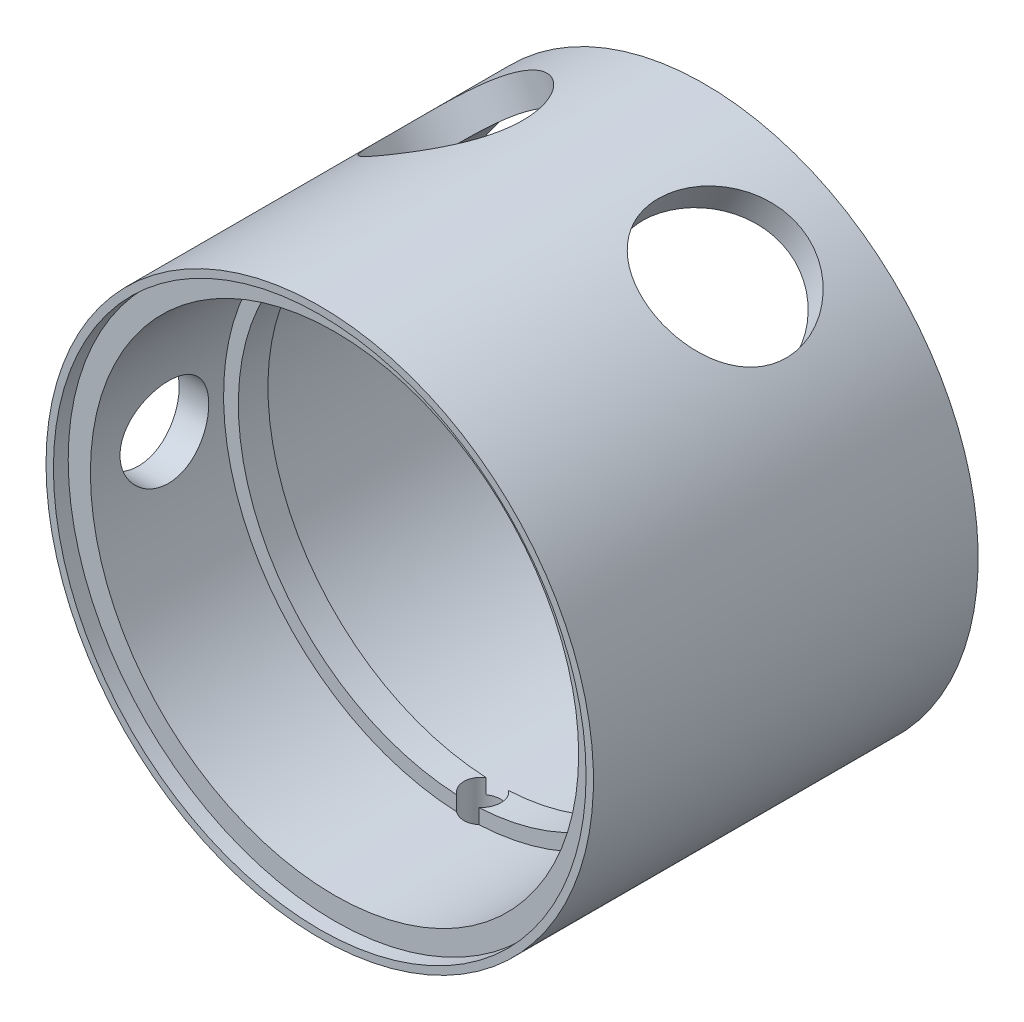
SolidWorks part; units mm, degrees
ref_plane "Front Plane" through (0, 0, 0) normal (0, 0, 1) x (1, 0, 0)
ref_plane "Top Plane" through (0, 0, 0) normal (0, 1, 0) x (1, 0, 0)
ref_plane "Right Plane" through (0, 0, 0) normal (1, 0, 0) x (0, 0, -1)
sketch "Sketch1" plane through (0, 0, 0) normal (0, 0, 1) x (1, 0, 0)
  circle A0 centre (0, 0) radius 19
  circle A1 centre (0, 0) radius 13.5
  dimension "D1" = 38
  dimension "D2" = 5.5
extrude "Boss-Extrude1" add sketch "Sketch1" along normal blind 26
sketch "Sketch2" plane through (0, 0, 0) normal (1, 0, 0) x (0, 0, -1)
  line L0 (-26, 19) -> (-26, 18.5)
  line L1 (-26, 19) -> (-26, -19) construction
  line L2 (-26, 18.5) -> (0, 18.5)
  line L3 (0, -19) -> (0, 19) construction
  line L4 (0, 18.5) -> (0, 19)
  line L5 (0, 19) -> (-26, 19)
  line L6 (0, 0) -> (-26, 0) construction
  dimension "D1" = 0.5
revolve "Cut-Revolve1" cut sketch "Sketch2" angle 360 about L6
sketch "Sketch3" plane through (0, 0, 0) normal (1, 0, 0) x (0, 0, -1)
  line L0 (0, 18) -> (0, 0)
  line L1 (-14, 15.5) -> (-14, 16.5)
  line L2 (-14, 16.5) -> (-1, 16.5)
  line L3 (-1, 16.5) -> (-1, 18)
  line L4 (-1, 18) -> (0, 18)
  line L5 (-26, 0) -> (0, 0) construction
  line L6 (-26, 18.5) -> (-26, -18.5) construction
  line L7 (0, -18.5) -> (0, 18.5) construction
  line L8 (-16, 15.5) -> (-16, 16.5)
  line L9 (-16, 16.5) -> (-25, 16.5)
  line L10 (-25, 16.5) -> (-25, 18)
  line L11 (-25, 18) -> (-26, 18)
  line L12 (-26, 18) -> (-26, 0)
  line L13 (-16, 15.5) -> (-14, 15.5)
  line L14 (-26, 0) -> (0, 0)
  dimension "D1" = 33
  dimension "D2" = 36
  dimension "D3" = 14
  dimension "D4" = 1
  dimension "D5" = 1
  dimension "D6" = 2
  dimension "D7" = 0.5
  dimension "D8" = 10
  dimension "D9" = 31
revolve "Cut-Revolve2" cut sketch "Sketch3" angle 360 about L5
ref_plane "Plane1" through (9.25, 16.0215, 0) normal (0.5, 0.866, 0) x (-0.866, 0.5, 0)
sketch "Sketch4" plane through (9.25, 16.0215, 0) normal (0.5, 0.866, 0) x (-0.866, 0.5, 0)
  line L0 (0, 26) -> (0, 0) construction
  line L1 (18, 26) -> (-18, 26) construction
  line L3 (-16.5, 14) -> (16.5, 14) construction
  circle A0 centre (0, 7.7) radius 5
  dimension "D1" = 10
  dimension "D2" = 6.3
extrude "Cut-Extrude1" cut sketch "Sketch4" against normal blind 10
mirror "Mirror1" about plane through (0, 0, 0) normal (1, 0, 0) of "Cut-Extrude1"
sketch "Sketch5" plane through (0, 0, 0) normal (0, 1, 0) x (1, 0, 0)
  line L0 (0, 0) -> (0, -26) construction
  line L2 (-18.5, -26) -> (18.5, -26) construction
  line L4 (-15.5, -16) -> (15.5, -16) construction
  circle A0 centre (0, -15) radius 1.25
  dimension "D2" = 2.5
  dimension "D1" = 1
extrude "Cut-Extrude4" cut sketch "Sketch5" against normal blind 20
sketch "Sketch6" plane through (0, 0, 0) normal (1, 0, 0) x (0, 0, -1)
  line L0 (0, 0) -> (-26, 0) construction
  line L1 (-26, 18.5) -> (-26, -18.5) construction
  circle A0 centre (-20, 0) radius 3
  dimension "D2" = 6
  dimension "D1" = 6
extrude "Cut-Extrude5" cut sketch "Sketch6" against normal blind 20
